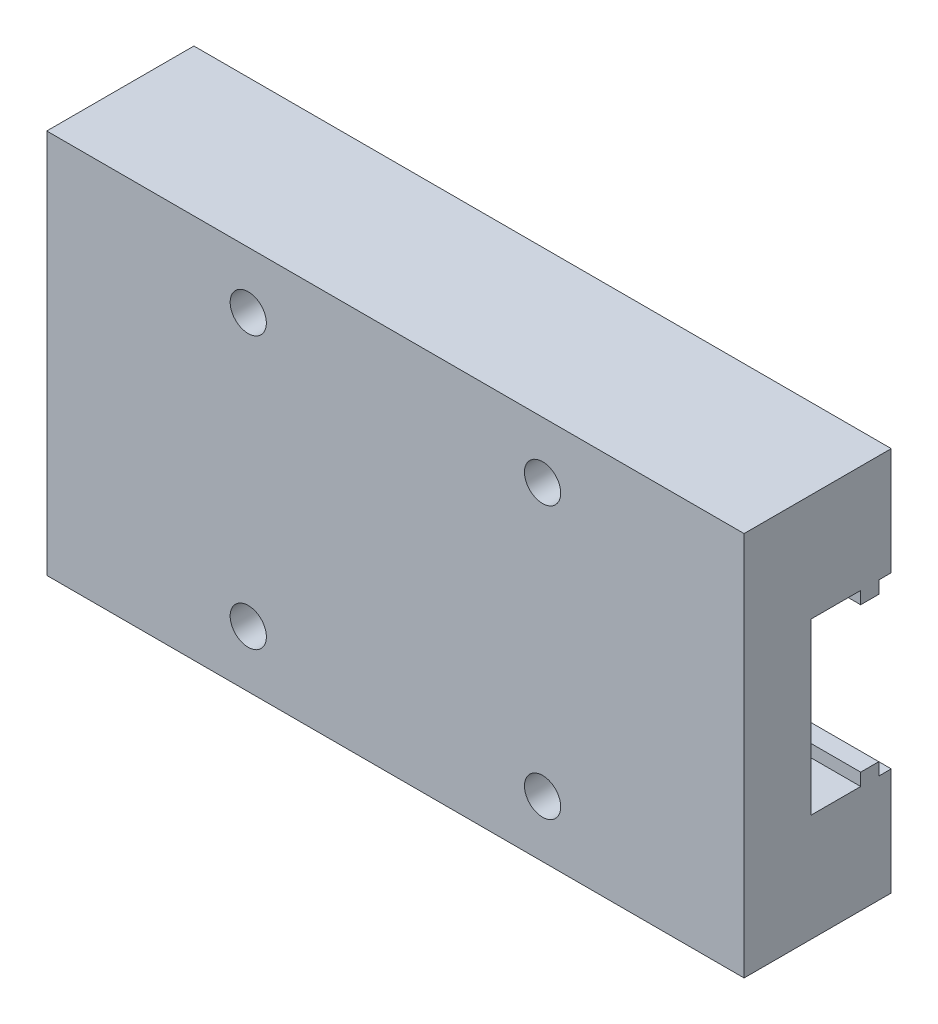
SolidWorks part; units mm, degrees
ref_plane "前视基准面" through (0, 0, 0) normal (0, 0, 1) x (1, 0, 0)
ref_plane "上视基准面" through (0, 0, 0) normal (0, 1, 0) x (1, 0, 0)
ref_plane "右视基准面" through (0, 0, 0) normal (1, 0, 0) x (0, 0, -1)
other "Configuration Table"
sketch "MGN7H 30.8 x 17 mm block profile" plane through (0, 0, 0) normal (0, 0, 1) x (1, 0, 0)
  line L0 (-6.9, 10.5) -> (23.9, 10.5)
  line L1 (23.9, 10.5) -> (23.9, 27.5)
  line L2 (23.9, 27.5) -> (-6.9, 27.5)
  line L3 (-6.9, 27.5) -> (-6.9, 10.5)
extrude "MGN7H 30.8 x 17 mm block" add sketch "MGN7H 30.8 x 17 mm block profile" along normal blind 6.5 from offset 33.9
sketch "Rail slot and running clearance profile" plane through (0, 0, 0) normal (0, 0, 1) x (1, 0, 0)
  line L0 (-7, 15.25) -> (24, 15.25)
  line L1 (24, 15.25) -> (24, 22.75)
  line L2 (24, 22.75) -> (-7, 22.75)
  line L3 (-7, 22.75) -> (-7, 15.25)
extrude "Rail slot and running clearance" cut sketch "Rail slot and running clearance profile" along normal blind 3.6 from offset 33.85
sketch "Nominal raceway shoulders profile" plane through (0, 0, 0) normal (0, 0, 1) x (1, 0, 0)
  line L0 (-6.9, 15.15) -> (23.9, 15.15)
  line L1 (23.9, 15.15) -> (23.9, 15.8)
  line L2 (23.9, 15.8) -> (-6.9, 15.8)
  line L3 (-6.9, 15.8) -> (-6.9, 15.15)
  line L4 (-6.9, 22.2) -> (23.9, 22.2)
  line L5 (23.9, 22.2) -> (23.9, 22.85)
  line L6 (23.9, 22.85) -> (-6.9, 22.85)
  line L7 (-6.9, 22.85) -> (-6.9, 22.2)
extrude "Nominal raceway shoulders" add sketch "Nominal raceway shoulders profile" along normal blind 0.8 from offset 34.45
sketch "M2 x 2.5 block holes 13 x 12 mm pitch profile" plane through (0, 0, 0) normal (0, 0, 1) x (1, 0, 0)
  circle A0 centre (2, 13) radius 0.8
  circle A1 centre (2, 25) radius 0.8
  circle A2 centre (15, 13) radius 0.8
  circle A3 centre (15, 25) radius 0.8
  point P8 (-8, 10)
  dimension "D3" = 1.6
  dimension "D6" = 1.6
  dimension "D9" = 1.6
  dimension "D12" = 1.6
  dimension "D1" = 10
  dimension "D2" = 3
  dimension "D4" = 10
  dimension "D5" = 15
  dimension "D7" = 23
  dimension "D8" = 3
  dimension "D10" = 23
  dimension "D11" = 15
extrude "M2 x 2.5 block holes 13 x 12 mm pitch" cut sketch "M2 x 2.5 block holes 13 x 12 mm pitch profile" along normal blind 2.6 from offset 37.9
